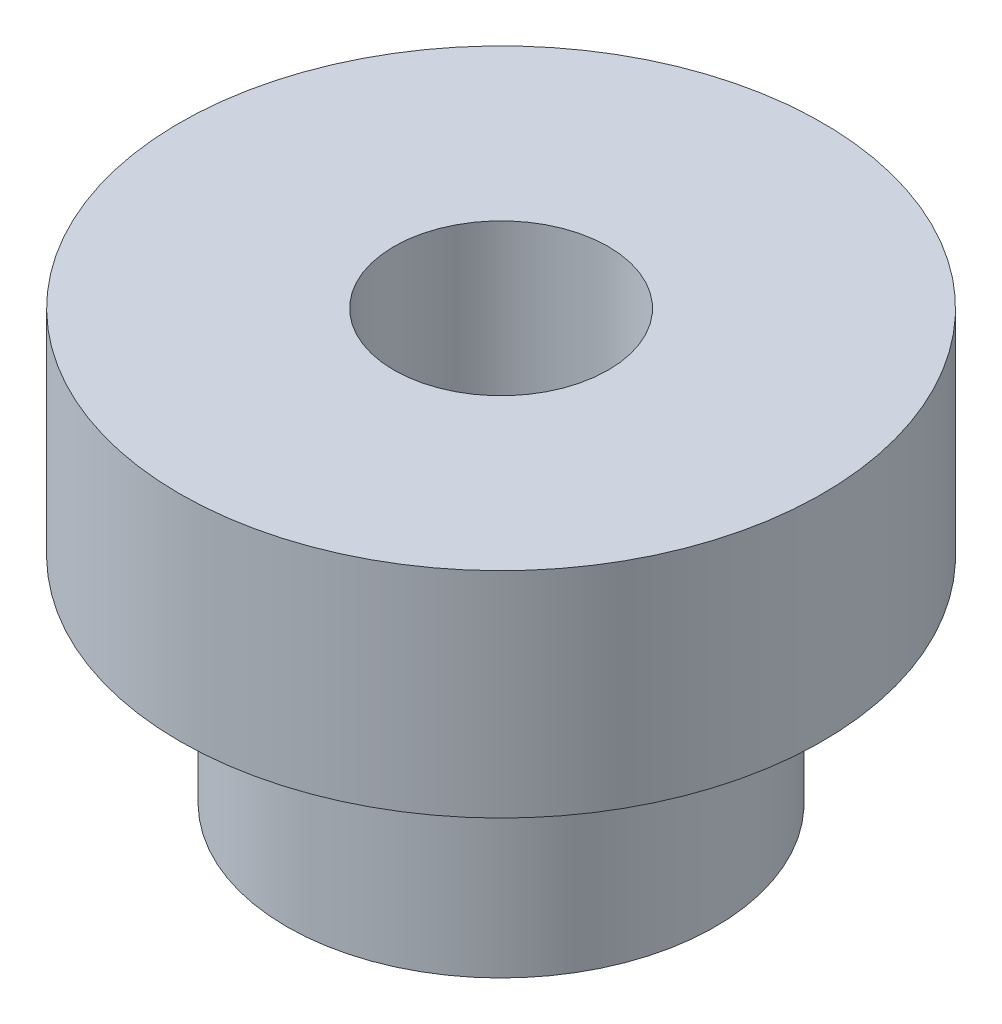
SolidWorks part; units mm, degrees
ref_plane "Front Plane" through (0, 0, 0) normal (0, 0, 1) x (1, 0, 0)
ref_plane "Top Plane" through (0, 0, 0) normal (0, 1, 0) x (1, 0, 0)
ref_plane "Right Plane" through (0, 0, 0) normal (1, 0, 0) x (0, 0, -1)
sketch "Sketch2" plane through (0, 0, 0) normal (0, 1, 0) x (1, 0, 0)
  circle A0 centre (0, 0) radius 1
  circle A1 centre (0, 0) radius 2
extrude "Boss-Extrude1" add sketch "Sketch2" along normal blind 2
sketch "Sketch3" plane through (0, 2, 0) normal (0, 1, 0) x (1, 0, 0)
  circle A0 centre (0, 0) radius 1
  circle A1 centre (0, 0) radius 3
extrude "Boss-Extrude2" add sketch "Sketch3" along normal blind 2
